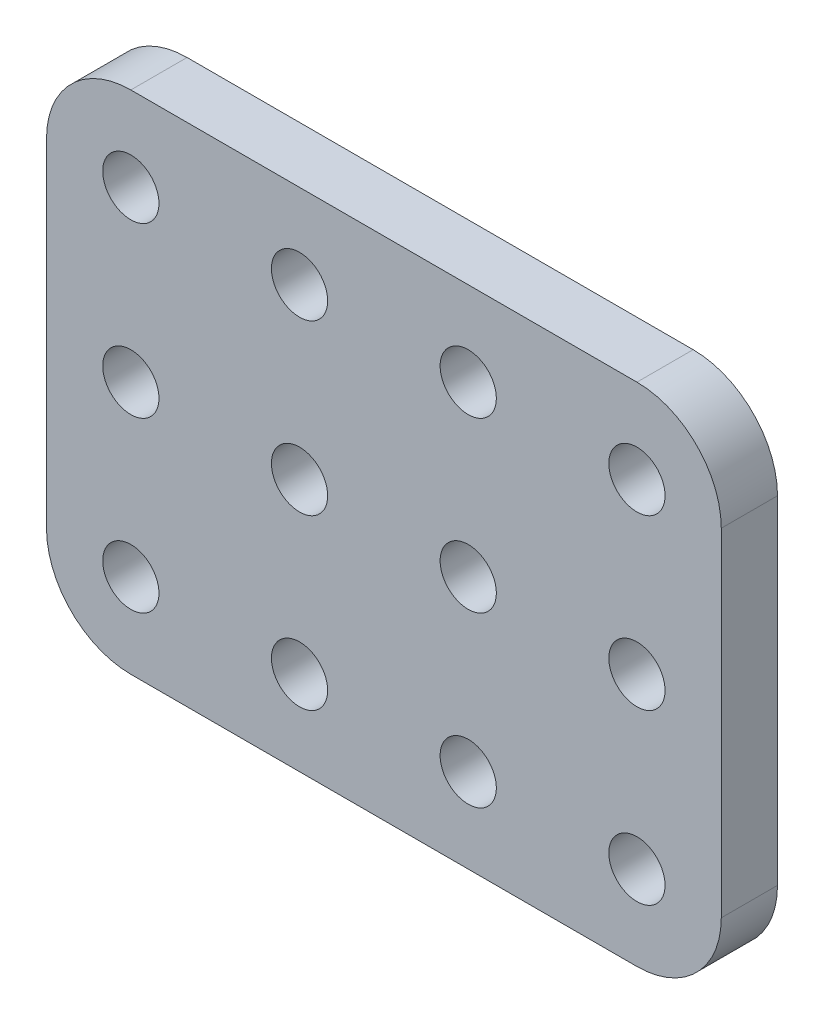
SolidWorks part; units mm, degrees
ref_plane "Alzado" through (0, 0, 0) normal (0, 0, 1) x (1, 0, 0)
ref_plane "Planta" through (0, 0, 0) normal (0, 1, 0) x (1, 0, 0)
ref_plane "Vista lateral" through (0, 0, 0) normal (1, 0, 0) x (0, 0, -1)
sketch "Model" plane through (0, 0, 0) normal (0, 0, 1) x (1, 0, 0)
  line L0 (-105.9434, 92.0565) -> (-105.9434, 74.0565)
  line L1 (-101.4434, 69.5565) -> (-74.4434, 69.5565)
  line L2 (-69.9434, 74.0565) -> (-69.9434, 92.0565)
  line L3 (-74.4434, 96.5565) -> (-101.4434, 96.5565)
  circle A0 centre (-101.4434, 92.0565) radius 1.5
  circle A1 centre (-92.4434, 92.0565) radius 1.5
  circle A2 centre (-83.4434, 92.0565) radius 1.5
  circle A3 centre (-74.4434, 92.0565) radius 1.5
  circle A4 centre (-101.4434, 83.0565) radius 1.5
  circle A5 centre (-92.4434, 83.0565) radius 1.5
  circle A6 centre (-83.4434, 83.0565) radius 1.5
  circle A7 centre (-74.4434, 83.0565) radius 1.5
  circle A8 centre (-101.4434, 74.0565) radius 1.5
  circle A9 centre (-92.4434, 74.0565) radius 1.5
  circle A10 centre (-83.4434, 74.0565) radius 1.5
  circle A11 centre (-74.4434, 74.0565) radius 1.5
  arc A12 (-101.4434, 96.5565) -> (-105.9434, 92.0565) centre (-101.4434, 92.0565) ccw
  arc A13 (-69.9434, 92.0565) -> (-74.4434, 96.5565) centre (-74.4434, 92.0565) ccw
  arc A14 (-105.9434, 74.0565) -> (-101.4434, 69.5565) centre (-101.4434, 74.0565) ccw
  arc A15 (-74.4434, 69.5565) -> (-69.9434, 74.0565) centre (-74.4434, 74.0565) ccw
extrude "Saliente-Extruir1" add sketch "Model" along normal blind 3
